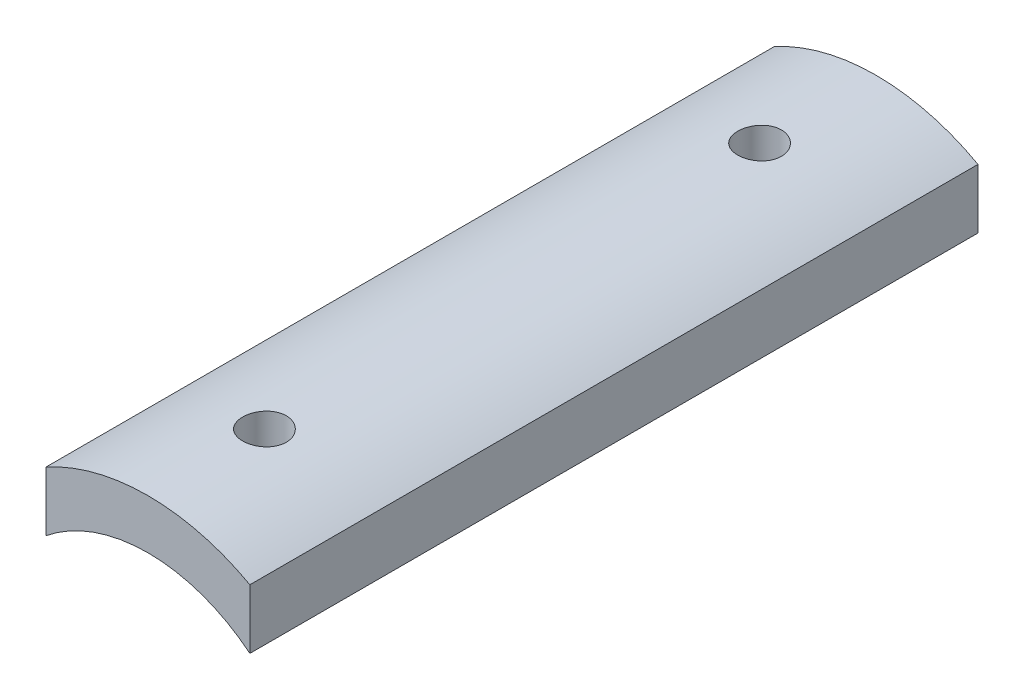
SolidWorks part; units mm, degrees
ref_plane "Front Plane" through (0, 0, 0) normal (0, 0, 1) x (1, 0, 0)
ref_plane "Top Plane" through (0, 0, 0) normal (0, 1, 0) x (1, 0, 0)
ref_plane "Right Plane" through (0, 0, 0) normal (1, 0, 0) x (0, 0, -1)
sketch "Sketch1" plane through (0, 0, 0) normal (0, 0, 1) x (1, 0, 0)
  line L0 (-7, 12.6984) -> (-7, 8.6145)
  line L1 (7, 12.6984) -> (7, 8.6145)
  arc A0 (7, 8.6145) -> (-7, 8.6145) centre (0, 0) ccw
  arc A1 (7, 12.6984) -> (-7, 12.6984) centre (0, 0) ccw
  dimension "D1" = 22.2
  dimension "D2" = 29
  dimension "D3" = 14
extrude "Boss-Extrude1" add sketch "Sketch1" along normal blind 50
sketch "Sketch7" plane through (0, 0, 0) normal (0, 1, 0) x (1, 0, 0)
  line L0 (0, -4.8317) -> (0, -41.4419) construction
  line L1 (7, 0) -> (-7, 0) construction
  line L2 (-7, -50) -> (7, -50) construction
  circle A0 centre (0, -8) radius 1.5
  circle A1 centre (0, -42) radius 1.5
  dimension "D1" = 3
  dimension "D2" = 8
  dimension "D3" = 8
extrude "Cut-Extrude2" cut sketch "Sketch7" against normal through all both and the other way through all
